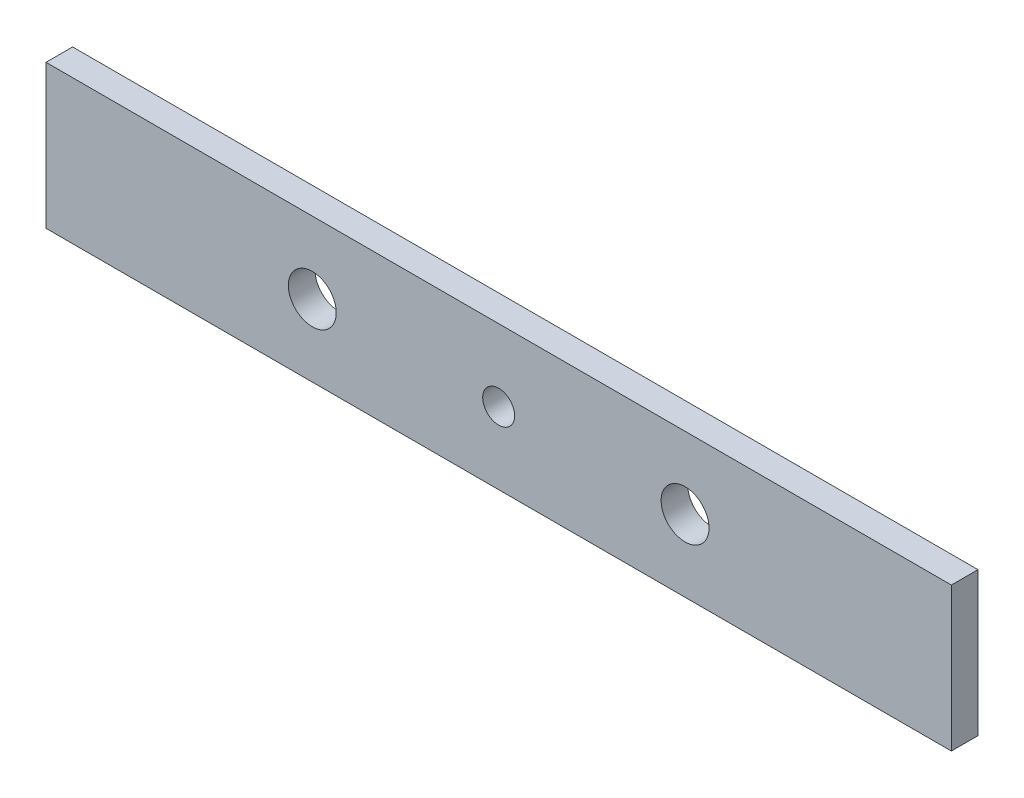
SolidWorks part; units mm, degrees
ref_plane "Front Plane" through (0, 0, 0) normal (0, 0, 1) x (1, 0, 0)
ref_plane "Top Plane" through (0, 0, 0) normal (0, 1, 0) x (1, 0, 0)
ref_plane "Right Plane" through (0, 0, 0) normal (1, 0, 0) x (0, 0, -1)
sketch "Sketch1" plane through (0, 0, 0) normal (0, 1, 0) x (1, 0, 0)
  line L1 (0, 0) -> (170, 0)
  line L2 (0, 0) -> (0, 5)
  line L3 (0, 5) -> (170, 5)
  line L4 (170, 0) -> (170, 5)
  dimension "D1" = 170
  dimension "D2" = 5
extrude "Boss-Extrude1" add sketch "Sketch1" along normal blind 27
sketch "Sketch2" plane through (0, 0, 0) normal (0, 0, 1) x (1, 0, 0)
  line L0 (0, 13.5) -> (170, 13.5) construction
  line L1 (0, 27) -> (0, 0) construction
  line L2 (170, 27) -> (170, 0) construction
  line L3 (85, 27) -> (85, 0) construction
  line L4 (0, 27) -> (170, 27) construction
  line L5 (0, 0) -> (170, 0) construction
  line L6 (50, 27) -> (50, 0) construction
  line L7 (120, 27) -> (120, 0) construction
  circle A0 centre (85, 13.5) radius 3
  circle A2 centre (120, 13.5) radius 4.5
  circle A3 centre (50, 13.5) radius 4.5
  dimension "D1" = 50
  dimension "D2" = 50
extrude "Cut-Extrude1" cut sketch "Sketch2" against normal blind 29
